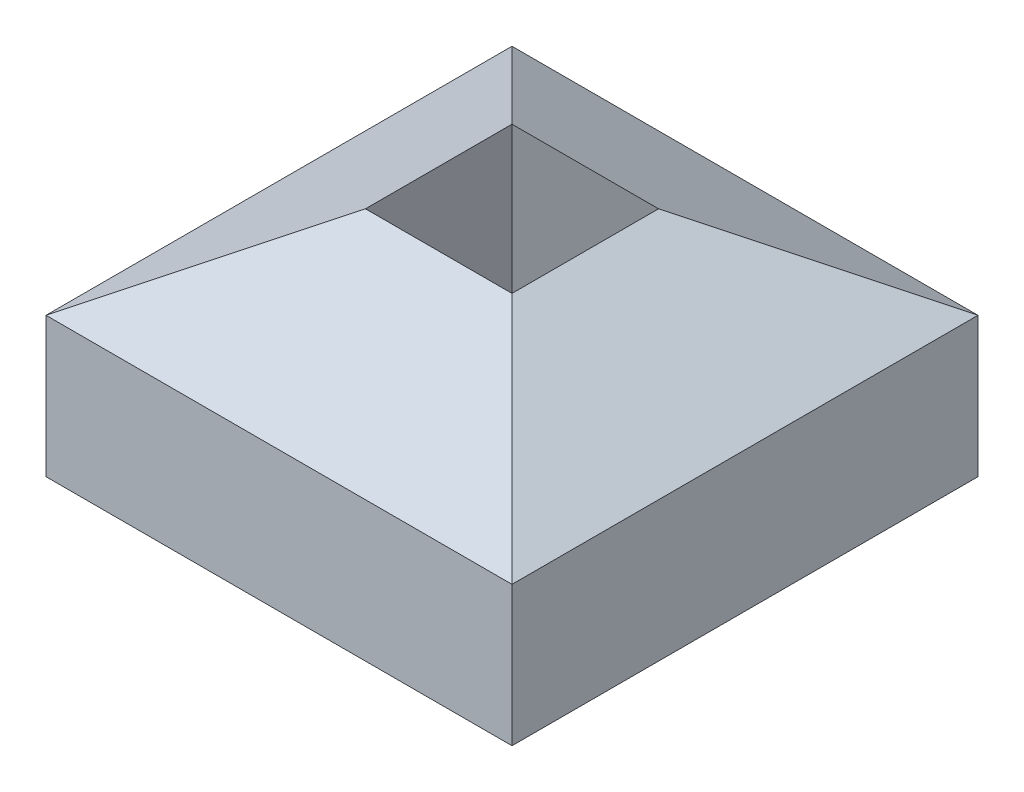
SolidWorks part; units mm, degrees
ref_plane "Front Plane" through (0, 0, 0) normal (0, 0, 1) x (1, 0, 0)
ref_plane "Top Plane" through (0, 0, 0) normal (0, 1, 0) x (1, 0, 0)
ref_plane "Right Plane" through (0, 0, 0) normal (1, 0, 0) x (0, 0, -1)
sketch "Sketch1" plane through (0, 0, 0) normal (0, 1, 0) x (1, 0, 0)
  line L1 (1270, -1270) -> (-1270, -1270)
  line L2 (1270, -1270) -> (1270, 1270)
  line L3 (1270, 1270) -> (-1270, 1270)
  line L4 (-1270, -1270) -> (-1270, 1270)
  line L5 (1270, -1270) -> (-1270, 1270) construction
  line L6 (1270, 1270) -> (-1270, -1270) construction
  point P0 (0, 0)
  dimension "D1" = 2540
  dimension "D2" = 2540
extrude "Boss-Extrude1" add sketch "Sketch1" along normal blind 762
sketch "Sketch2" plane through (0, 762, 0) normal (0, 1, 0) x (1, 0, 0)
  line L1 (-1270, 1270) -> (1270, 1270)
  line L2 (-1270, 1270) -> (-1270, -1270)
  line L3 (-1270, -1270) -> (1270, -1270)
  line L4 (1270, 1270) -> (1270, -1270)
  line L5 (381, -381) -> (-381, -381)
  line L6 (381, -381) -> (381, 381)
  line L7 (381, 381) -> (-381, 381)
  line L8 (-381, -381) -> (-381, 381)
  line L9 (381, -381) -> (-381, 381) construction
  line L10 (381, 381) -> (-381, -381) construction
  point P6 (0, 0)
  dimension "D1" = 762
  dimension "D2" = 762
extrude "Boss-Extrude2" add sketch "Sketch2" along normal blind 508 contours L8 L7 L6 L5
sketch "Sketch4" plane through (0, 762, 0) normal (0, 1, 0) x (1, 0, 0)
  line L1 (-1270, 1270) -> (1270, 1270)
  line L2 (-1270, 1270) -> (-1270, -1270)
  line L3 (-1270, -1270) -> (1270, -1270)
  line L4 (1270, 1270) -> (1270, -1270)
extrude "Boss-Extrude3" add sketch "Sketch4" along normal blind 508 draft 60
sketch "Sketch5" plane through (0, 0, 0) normal (0, -1, 0) x (1, 0, 0)
  line L1 (762, -762) -> (-762, -762)
  line L2 (762, -762) -> (762, 762)
  line L3 (762, 762) -> (-762, 762)
  line L4 (-762, -762) -> (-762, 762)
  line L5 (762, -762) -> (-762, 762) construction
  line L6 (762, 762) -> (-762, -762) construction
  point P0 (0, 0)
  dimension "D1" = 1524
  dimension "D2" = 1524
extrude "Cut-Extrude1" cut sketch "Sketch5" against normal blind 1270 draft 16
